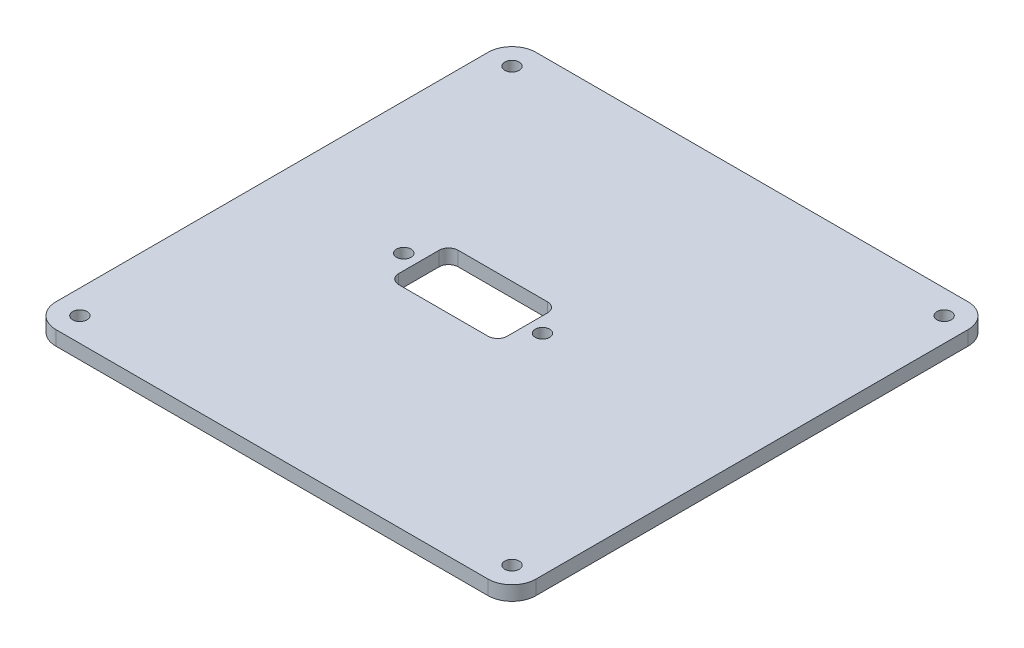
SolidWorks part; units mm, degrees
material "普通碳钢"
ref_plane "前视基准面" through (0, 0, 0) normal (0, 0, 1) x (1, 0, 0)
ref_plane "上视基准面" through (0, 0, 0) normal (0, 1, 0) x (1, 0, 0)
ref_plane "右视基准面" through (0, 0, 0) normal (1, 0, 0) x (0, 0, -1)
sketch "草图1" plane through (0, 0, 0) normal (0, 1, 0) x (1, 0, 0)
  line L1 (-45, 50) -> (45, 50)
  line L2 (-50, 45) -> (-50, -45)
  line L3 (-45, -50) -> (45, -50)
  line L4 (50, 45) -> (50, -45)
  line L5 (-50, 50) -> (50, -50) construction
  line L6 (-50, -50) -> (50, 50) construction
  line L7 (-17.4, 6.2) -> (1.2, 6.2)
  line L8 (-19.4, 4.2) -> (-19.4, -4.2)
  line L9 (-17.4, -6.2) -> (1.2, -6.2)
  line L10 (3.2, 4.2) -> (3.2, -4.2)
  arc A0 (50, -45) -> (45, -50) centre (45, -45) cw
  arc A1 (-45, -50) -> (-50, -45) centre (-45, -45) cw
  arc A2 (-45, 50) -> (-50, 45) centre (-45, 45) ccw
  arc A3 (45, 50) -> (50, 45) centre (45, 45) cw
  circle A4 centre (-45, 45) radius 1.5
  circle A5 centre (45, 45) radius 1.5
  circle A6 centre (-45, -45) radius 1.5
  circle A7 centre (45, -45) radius 1.5
  circle A8 centre (6.345, 0) radius 1.5
  circle A10 centre (-22.545, 0) radius 1.5
  arc A12 (3.2, -4.2) -> (1.2, -6.2) centre (1.2, -4.2) cw
  arc A13 (3.2, 4.2) -> (1.2, 6.2) centre (1.2, 4.2) ccw
  arc A14 (-17.4, -6.2) -> (-19.4, -4.2) centre (-17.4, -4.2) cw
  arc A15 (-17.4, 6.2) -> (-19.4, 4.2) centre (-17.4, 4.2) ccw
  point P0 (0, 0)
  dimension "D3" = 5
  dimension "D4" = 6.2
  dimension "D12" = 3
  dimension "D13" = 2
  dimension "D1" = 100
  dimension "D2" = 100
  dimension "D5" = 6.2
  dimension "D6" = 19.4
  dimension "D7" = 3.2
  dimension "D8" = 22.545
  dimension "D9" = 28.89
  dimension "D10" = 0
extrude "凸台-拉伸1" add sketch "草图1" along normal blind 3
